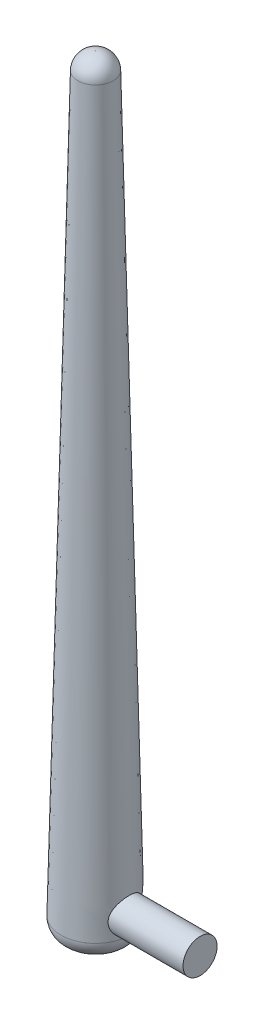
SolidWorks part; units mm, degrees
ref_plane "Front Plane" through (0, 0, 0) normal (0, 0, 1) x (1, 0, 0)
ref_plane "Top Plane" through (0, 0, 0) normal (0, 1, 0) x (1, 0, 0)
ref_plane "Right Plane" through (0, 0, 0) normal (1, 0, 0) x (0, 0, -1)
sketch "Sketch1" plane through (0, 0, 0) normal (0, 0, 1) x (1, 0, 0)
  line L0 (0, 0) -> (0, 110)
  line L1 (0, 0) -> (5, 0)
  line L2 (0, 110) -> (2.5, 110)
  line L3 (5, 0) -> (2.5, 110)
revolve "Revolve1" add sketch "Sketch1" angle 360 about L0
fillet "Fillet1" radius 2.5 2 edges at (0, 0, -5) (0, 110, -2.5)
sketch "Sketch2" plane through (0, 0, 0) normal (1, 0, 0) x (0, 0, -1)
  circle A0 centre (0, 5) radius 2.4432
extrude "Boss-Extrude1" add sketch "Sketch2" along normal blind 15
